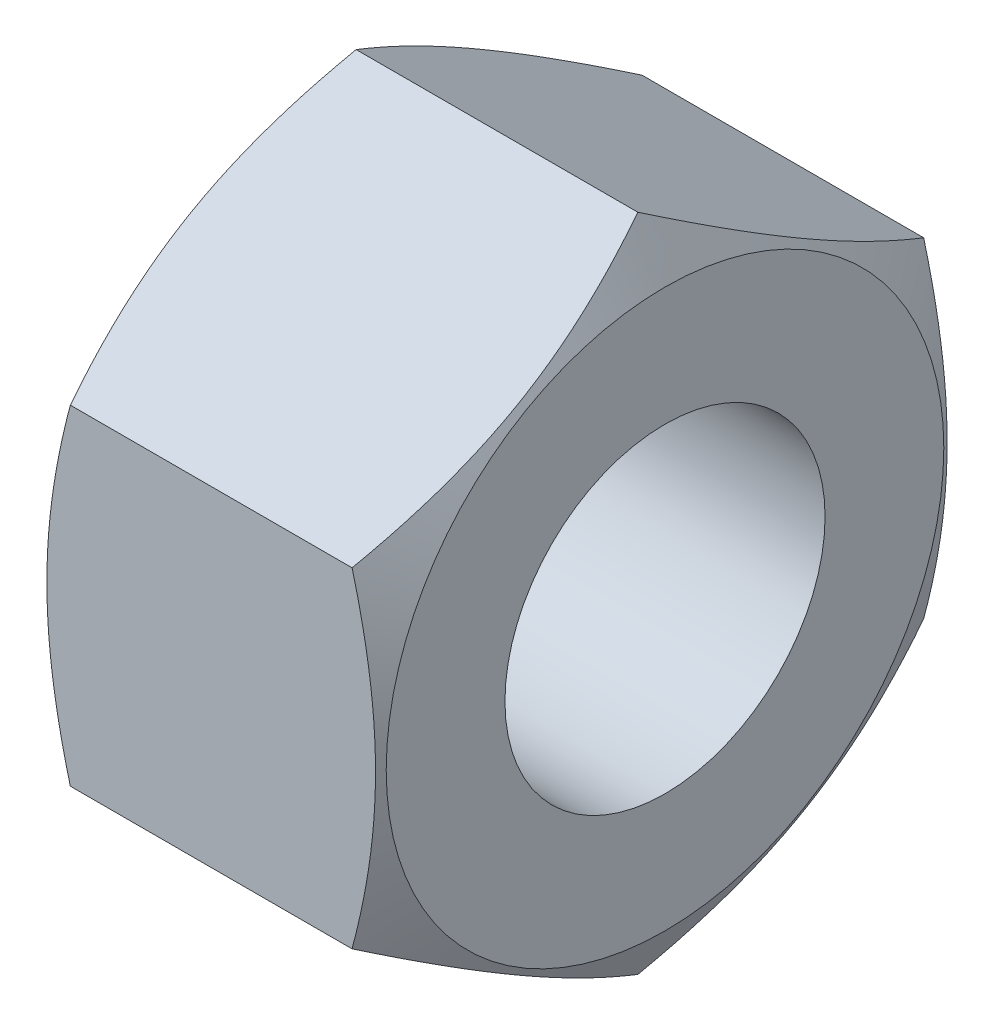
SolidWorks part; units mm, degrees
material "AISI 1045 Steel, cold drawn"
ref_plane "Front Plane" through (0, 0, 0) normal (0, 0, 1) x (1, 0, 0)
ref_plane "Top Plane" through (0, 0, 0) normal (0, 1, 0) x (1, 0, 0)
ref_plane "Right Plane" through (0, 0, 0) normal (1, 0, 0) x (0, 0, -1)
sketch "Sketch1" plane through (0, 0, 0) normal (1, 0, 0) x (0, 0, -1)
  line L1 (0, 8.1829) -> (-7.0866, 4.0915)
  line L2 (-7.0866, 4.0915) -> (-7.0866, -4.0915)
  line L3 (-7.0866, -4.0915) -> (0, -8.1829)
  line L4 (0, -8.1829) -> (7.0866, -4.0915)
  line L5 (7.0866, -4.0915) -> (7.0866, 4.0915)
  line L6 (7.0866, 4.0915) -> (0, 8.1829)
  circle A0 centre (0, 0) radius 7.0866 construction
  dimension "D1" = 14.1732
extrude "BASE" add sketch "Sketch1" along normal mid plane 8.3312
sketch "Sketch2" plane through (0, 0, 0) normal (0, 0, 1) x (1, 0, 0)
  line L0 (4.1656, 6.9129) -> (3.4929, 8.1829)
  line L1 (4.1656, 8.1829) -> (4.1656, 4.0915) construction
  line L2 (4.1656, 8.1829) -> (-4.1656, 8.1829) construction
  line L3 (3.4929, 8.1829) -> (4.1656, 8.1829)
  line L4 (4.1656, 8.1829) -> (4.1656, 6.9129)
  line L6 (0, 0) -> (9.619, 0) construction
  dimension "D1" = 0.6727
  dimension "D2" = 1.27
revolve "EDGE-CUT" cut sketch "Sketch2" angle 360 about L6
mirror "Mirror1" about plane through (0, 0, 0) normal (1, 0, 0) of "EDGE-CUT"
hole_wizard "3/8-16 Tapped Hole1" positions "Sketch4" profile "Sketch3" tap size "3/8-16" standard "Ansi Inch" end condition through all
sketch "Sketch4" plane through (4.1656, 0, 0) normal (1, 0, 0) x (0, 0, -1)
  point P0 (0, 0)
sketch "Sketch3" plane through (4.1656, 0, 0) normal (0, 1, 0) x (0, 0, -1)
  line L0 (0, 0) -> (0, 8.3312)
  line L1 (0, 8.3312) -> (3.9687, 8.3312)
  line L2 (3.9687, 8.3312) -> (3.9687, 0)
  line L5 (3.9687, 0) -> (0, 0)
  line L11 (0, -6.35) -> (0, 107.95) construction
  dimension "Thru Tap Drill Dia." = 7.9375
  dimension "Thru Tap Drill Depth" = 8.3312
cosmetic thread "Hole Thread1" parameters "D2"=9.525
